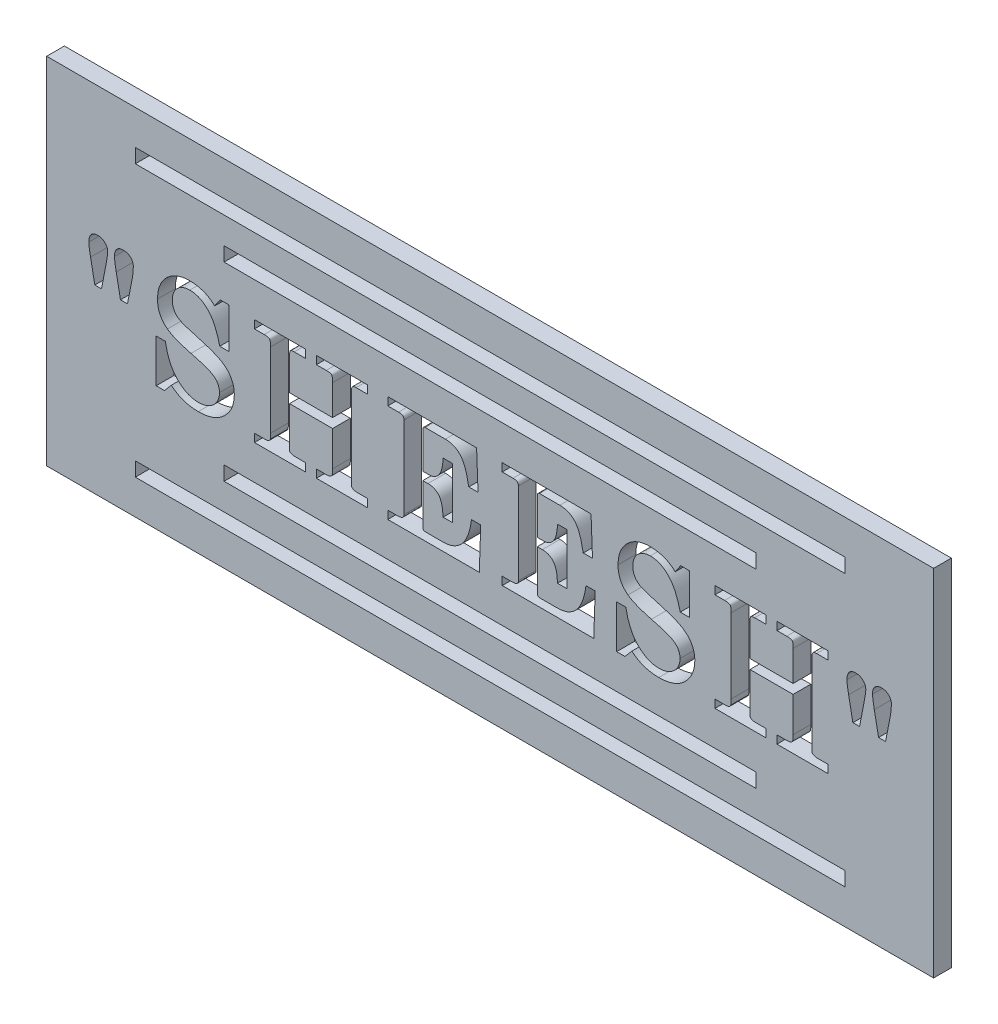
SolidWorks part; units mm, degrees
ref_plane "Front Plane" through (0, 0, 0) normal (0, 0, 1) x (1, 0, 0)
ref_plane "Top Plane" through (0, 0, 0) normal (0, 1, 0) x (1, 0, 0)
ref_plane "Right Plane" through (0, 0, 0) normal (1, 0, 0) x (0, 0, -1)
sketch "Sketch1" plane through (0, 0, 0) normal (0, 0, 1) x (1, 0, 0)
  line L0 (-230, -30) -> (230, -30) construction
  line L1 (-250, 100) -> (250, 100)
  line L2 (-250, 100) -> (-250, -100)
  line L3 (-250, -100) -> (250, -100)
  line L4 (250, 100) -> (250, -100)
  line L5 (-250, 100) -> (250, -100) construction
  line L6 (-250, -100) -> (250, 100) construction
  line L7 (-230, 30) -> (230, 30) construction
  line L8 (-230, 30) -> (230, -30) construction
  line L9 (-250, 0) -> (250, 0) construction
  line L10 (-200, 80.5) -> (200, 80.5)
  line L11 (-200, 80.5) -> (-200, 72.5)
  line L12 (-200, 72.5) -> (200, 72.5)
  line L13 (200, 80.5) -> (200, 72.5)
  line L14 (150, 49.5) -> (150, 30) construction
  line L15 (-150, 57.5) -> (150, 57.5)
  line L16 (-150, 57.5) -> (-150, 49.5)
  line L17 (-150, 49.5) -> (150, 49.5)
  line L18 (150, 57.5) -> (150, 49.5)
  line L19 (200, 80.5) -> (200, 100) construction
  line L20 (-200, -72.5) -> (200, -72.5)
  line L21 (200, -80.5) -> (200, -72.5)
  line L22 (-200, -80.5) -> (200, -80.5)
  line L23 (-200, -80.5) -> (-200, -72.5)
  line L24 (-150, -49.5) -> (150, -49.5)
  line L25 (150, -57.5) -> (150, -49.5)
  line L26 (-150, -57.5) -> (150, -57.5)
  line L27 (-150, -57.5) -> (-150, -49.5)
  text T0 "\"SHEESH\"" font "Century" height 60
  point P0 (0, 0)
  point P21 (0, 57.5)
  point P22 (0, 80.5)
  dimension "D1" = 500
  dimension "D2" = 200
  dimension "D3" = 60
  dimension "D4" = 460
  dimension "D5" = 300
  dimension "D6" = 400
  dimension "D8" = 8
  dimension "D9" = 15
extrude "Boss-Extrude1" add sketch "Sketch1" along normal blind 10
